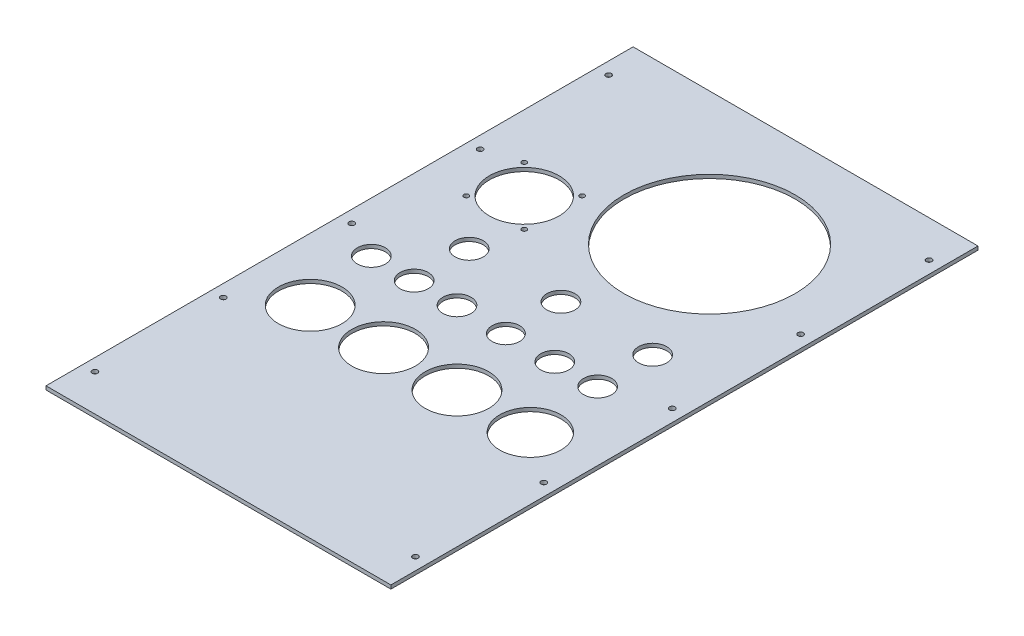
SolidWorks part; units mm, degrees
ref_plane "Front" through (0, 0, 0) normal (0, 0, 1) x (1, 0, 0)
ref_plane "Top" through (0, 0, 0) normal (0, 1, 0) x (1, 0, 0)
ref_plane "Right" through (0, 0, 0) normal (1, 0, 0) x (0, 0, -1)
sketch "Sketch1" plane through (0, 0, 0) normal (0, 1, 0) x (1, 0, 0)
  line L1 (0, 0) -> (282, 0)
  line L2 (0, 0) -> (0, 480)
  line L3 (0, 480) -> (282, 480)
  line L4 (282, 0) -> (282, 480)
  dimension "D1" = 282
  dimension "D2" = 480
extrude "Boss-Extrude1" add sketch "Sketch1" along normal blind 3
sketch "Sketch2" plane through (0, 3, 0) normal (0, 1, 0) x (1, 0, 0)
  line L0 (282, 480) -> (0, 480) construction
  line L2 (61, 202.5) -> (91, 202.5) construction
  line L3 (26, 202.5) -> (56, 202.5) construction
  line L4 (26, 202.5) -> (26, 247.5) construction
  line L5 (26, 247.5) -> (56, 247.5) construction
  line L6 (56, 202.5) -> (56, 247.5) construction
  line L7 (26, 202.5) -> (56, 247.5) construction
  line L8 (26, 247.5) -> (56, 202.5) construction
  line L9 (61, 202.5) -> (61, 247.5) construction
  line L10 (61, 247.5) -> (91, 247.5) construction
  line L11 (91, 202.5) -> (91, 247.5) construction
  line L12 (61, 202.5) -> (91, 247.5) construction
  line L13 (61, 247.5) -> (91, 202.5) construction
  line L14 (96, 202.5) -> (126, 202.5) construction
  line L15 (96, 202.5) -> (96, 247.5) construction
  line L16 (96, 247.5) -> (126, 247.5) construction
  line L17 (126, 202.5) -> (126, 247.5) construction
  line L18 (96, 202.5) -> (126, 247.5) construction
  line L19 (96, 247.5) -> (126, 202.5) construction
  line L20 (61, 247.5) -> (91, 247.5) construction
  line L21 (61, 247.5) -> (61, 292.5) construction
  line L22 (61, 292.5) -> (91, 292.5) construction
  line L23 (91, 247.5) -> (91, 292.5) construction
  line L24 (61, 247.5) -> (91, 292.5) construction
  line L25 (61, 292.5) -> (91, 247.5) construction
  line L26 (128.5, 255) -> (173.5, 255) construction
  line L27 (128.5, 255) -> (128.5, 285) construction
  line L28 (128.5, 285) -> (173.5, 285) construction
  line L29 (173.5, 255) -> (173.5, 285) construction
  line L30 (128.5, 255) -> (173.5, 285) construction
  line L31 (128.5, 285) -> (173.5, 255) construction
  line L32 (176, 202.5) -> (206, 202.5) construction
  line L33 (176, 202.5) -> (176, 247.5) construction
  line L34 (176, 247.5) -> (206, 247.5) construction
  line L35 (206, 202.5) -> (206, 247.5) construction
  line L36 (176, 202.5) -> (206, 247.5) construction
  line L37 (176, 247.5) -> (206, 202.5) construction
  line L38 (211, 247.5) -> (241, 247.5) construction
  line L39 (211, 247.5) -> (211, 292.5) construction
  line L40 (211, 292.5) -> (241, 292.5) construction
  line L41 (241, 247.5) -> (241, 292.5) construction
  line L42 (211, 247.5) -> (241, 292.5) construction
  line L43 (211, 292.5) -> (241, 247.5) construction
  line L44 (211, 202.5) -> (241, 202.5) construction
  line L45 (211, 202.5) -> (211, 247.5) construction
  line L46 (211, 247.5) -> (241, 247.5) construction
  line L47 (241, 202.5) -> (241, 247.5) construction
  line L48 (211, 202.5) -> (241, 247.5) construction
  line L49 (211, 247.5) -> (241, 202.5) construction
  line L50 (0, 480) -> (0, 0) construction
  circle A0 centre (171, 371.5) radius 70
  circle A1 centre (61, 330) radius 28.5
  circle A2 centre (231, 165) radius 25
  circle A3 centre (171, 165) radius 26
  circle A4 centre (111, 165) radius 26
  circle A5 centre (51, 165) radius 26
  circle A6 centre (41, 225) radius 11.5
  circle A7 centre (76, 225) radius 11.5
  circle A8 centre (111, 225) radius 11.5
  circle A9 centre (76, 270) radius 11.5
  circle A10 centre (151, 270) radius 11.5
  circle A11 centre (191, 225) radius 11.5
  circle A12 centre (226, 270) radius 11.5
  circle A13 centre (226, 225) radius 11.5
  circle A14 centre (151, 225) radius 11.25
  circle A15 centre (151, 225) radius 24 construction
  point P28 (141, 165)
  dimension "D1" = 140
  dimension "D2" = 57
  dimension "D3" = 50
  dimension "D4" = 52
  dimension "D5" = 52
  dimension "D8" = 52
  dimension "D16" = 23
  dimension "D19" = 23
  dimension "D21" = 23
  dimension "D23" = 23
  dimension "D25" = 23
  dimension "D27" = 23
  dimension "D29" = 23
  dimension "D31" = 23
  dimension "D46" = 22.5
  dimension "D47" = 48
  dimension "D6" = 60
  dimension "D7" = 60
  dimension "D9" = 60
  dimension "D10" = 0
  dimension "D11" = 0
  dimension "D12" = 0
  dimension "D13" = 141
  dimension "D14" = 0
  dimension "D15" = 110
  dimension "D17" = 30
  dimension "D18" = 45
  dimension "D20" = 30
  dimension "D22" = 30
  dimension "D24" = 30
  dimension "D26" = 45
  dimension "D28" = 30
  dimension "D30" = 30
  dimension "D32" = 30
  dimension "D33" = 35
  dimension "D34" = 35
  dimension "D35" = 45
  dimension "D36" = 45
  dimension "D37" = 45
  dimension "D38" = 45
  dimension "D39" = 60
  dimension "D40" = 45
  dimension "D41" = 30
  dimension "D42" = 45
  dimension "D43" = 45
  dimension "D44" = 35
  dimension "D45" = 45
  dimension "D48" = 40
  dimension "D49" = 30
  dimension "D50" = 40
  dimension "D51" = 0
  dimension "D53" = 45
  dimension "D54" = 41.5
  dimension "D55" = 60
  dimension "D56" = 315
  dimension "D57" = 10
  dimension "D58" = 0
  dimension "D59" = 30
extrude "Cut-Extrude1" cut sketch "Sketch2" against normal up to next
hole_wizard "Ø4.5 (4.5) Diameter Hole1" positions "Sketch5" profile "Sketch6" hole size "Ø4.5" standard "DIN" end condition up to next
sketch "Sketch5" plane through (0, 0, 0) normal (0, -1, 0) x (-1, 0, 0)
  line L0 (-282, 0) -> (-282, 480) construction
  line L1 (-282, 480) -> (0, 480) construction
  line L2 (0, 480) -> (0, 0) construction
  line L3 (0, 0) -> (-282, 0) construction
  point P0 (-272, 450)
  point P16 (-272, 345)
  point P17 (-272, 240)
  point P18 (-272, 135)
  point P19 (-272, 30)
  point P20 (-10, 345)
  point P21 (-10, 240)
  point P22 (-10, 135)
  point P23 (-10, 30)
  point P24 (-10, 450)
  dimension "D1" = 10
  dimension "D2" = 30
  dimension "D5" = 10
  dimension "D6" = 30
  dimension "D7" = 105
  dimension "D3" = 5
  dimension "D4" = 2
sketch "Sketch6" plane through (272, 0, -450) normal (1, 0, 0) x (0, 0, -1)
  line L0 (0, 0) -> (0, 3)
  line L1 (0, 3) -> (2.25, 3)
  line L2 (2.25, 3) -> (2.25, 0)
  line L5 (2.25, 0) -> (0, 0)
  line L11 (0, -6.35) -> (0, 107.95) construction
  dimension "Thru Hole Dia." = 4.5
  dimension "Thru Hole Depth" = 3
hole_wizard "Ø4.0 (4) Diameter Hole1" positions "Sketch9" profile "Sketch8" hole size "Ø4.0" standard "DIN" end condition up to next
sketch "Sketch9" plane through (0, 0, 0) normal (0, -1, 0) x (-1, 0, 0)
  line L0 (-61, 330) -> (-19.404, 371.596) construction
  circle A0 centre (-61, 330) radius 33.5 construction
  point P10 (-37.3119, 353.6881)
  point P17 (-37.3119, 306.3119)
  point P18 (-84.6881, 306.3119)
  point P19 (-84.6881, 353.6881)
  dimension "D1" = 67
  dimension "D2" = 4
sketch "Sketch8" plane through (84.6881, 0, -353.6881) normal (1, 0, 0) x (0, 0, -1)
  line L0 (0, 0) -> (0, 3)
  line L1 (0, 3) -> (2, 3)
  line L2 (2, 3) -> (2, 0)
  line L5 (2, 0) -> (0, 0)
  line L11 (0, -6.35) -> (0, 107.95) construction
  dimension "Thru Hole Dia." = 4
  dimension "Thru Hole Depth" = 3
equation "\"Instrument Spacing\"= 60mm"
equation "\"Skirt\"= 25mm"
equation "\"Instrument Diameter\"= 52mm"
equation "\"N_Instruments\"= 4"
equation "\"Panel Width\"= ( \"N_Instruments\" - 1 ) * \"Instrument Spacing\" + \"Instrument Diameter\" + 2 * \"Skirt\""
